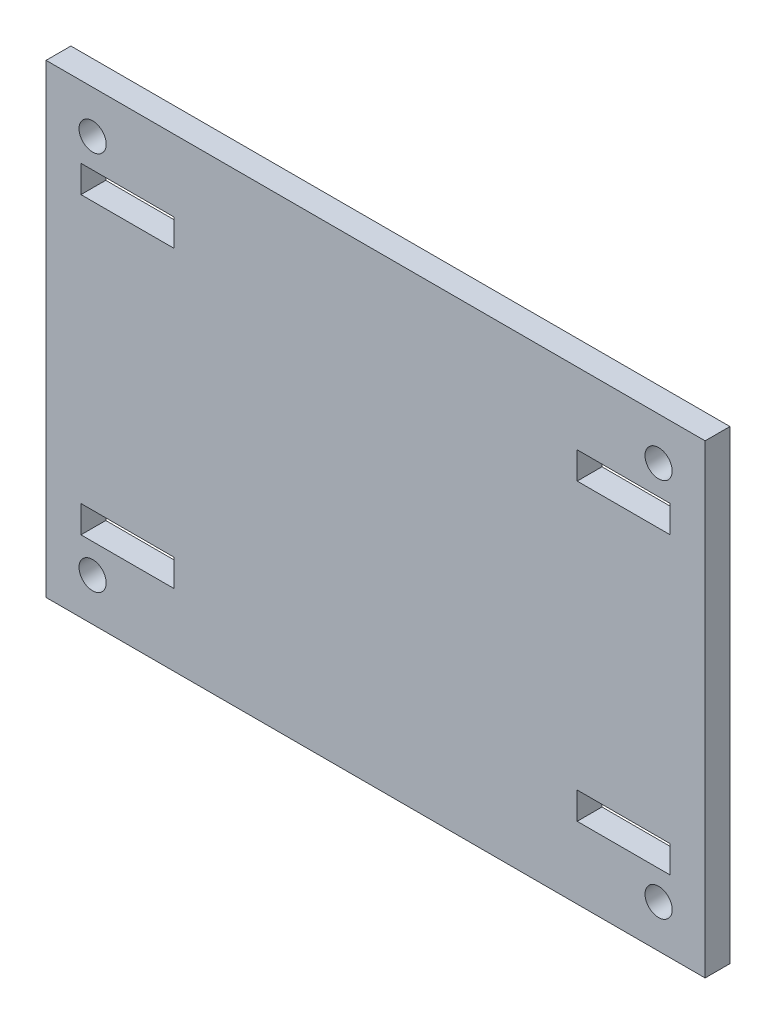
SolidWorks part; units mm, degrees
ref_plane "Front Plane" through (0, 0, 0) normal (0, 0, 1) x (1, 0, 0)
ref_plane "Top Plane" through (0, 0, 0) normal (0, 1, 0) x (1, 0, 0)
ref_plane "Right Plane" through (0, 0, 0) normal (1, 0, 0) x (0, 0, -1)
sketch "Sketch1" plane through (0, 0, 0) normal (0, 0, 1) x (1, 0, 0)
  line L1 (-42.5, -30) -> (42.5, -30)
  line L2 (-42.5, -30) -> (-42.5, 30)
  line L3 (-42.5, 30) -> (42.5, 30)
  line L4 (42.5, -30) -> (42.5, 30)
  line L6 (-38, 17.25) -> (-26, 17.25)
  line L7 (-38, 17.25) -> (-38, 20.75)
  line L8 (-38, 20.75) -> (-26, 20.75)
  line L9 (-26, 17.25) -> (-26, 20.75)
  line L11 (26, 17.25) -> (38, 17.25)
  line L12 (26, 17.25) -> (26, 20.75)
  line L13 (26, 20.75) -> (38, 20.75)
  line L14 (38, 17.25) -> (38, 20.75)
  line L16 (-38, -20.75) -> (-26, -20.75)
  line L17 (-38, -20.75) -> (-38, -17.25)
  line L18 (-38, -17.25) -> (-26, -17.25)
  line L19 (-26, -20.75) -> (-26, -17.25)
  line L21 (26, -20.75) -> (38, -20.75)
  line L22 (26, -20.75) -> (26, -17.25)
  line L23 (26, -17.25) -> (38, -17.25)
  line L24 (38, -20.75) -> (38, -17.25)
  circle A0 centre (-36.5, -24.5) radius 1.75
  circle A1 centre (36.5, -24.5) radius 1.75
  circle A2 centre (-36.5, 24.5) radius 1.75
  circle A3 centre (36.5, 24.5) radius 1.75
extrude "Electronics deck" add sketch "Sketch1" along normal blind 3.2
